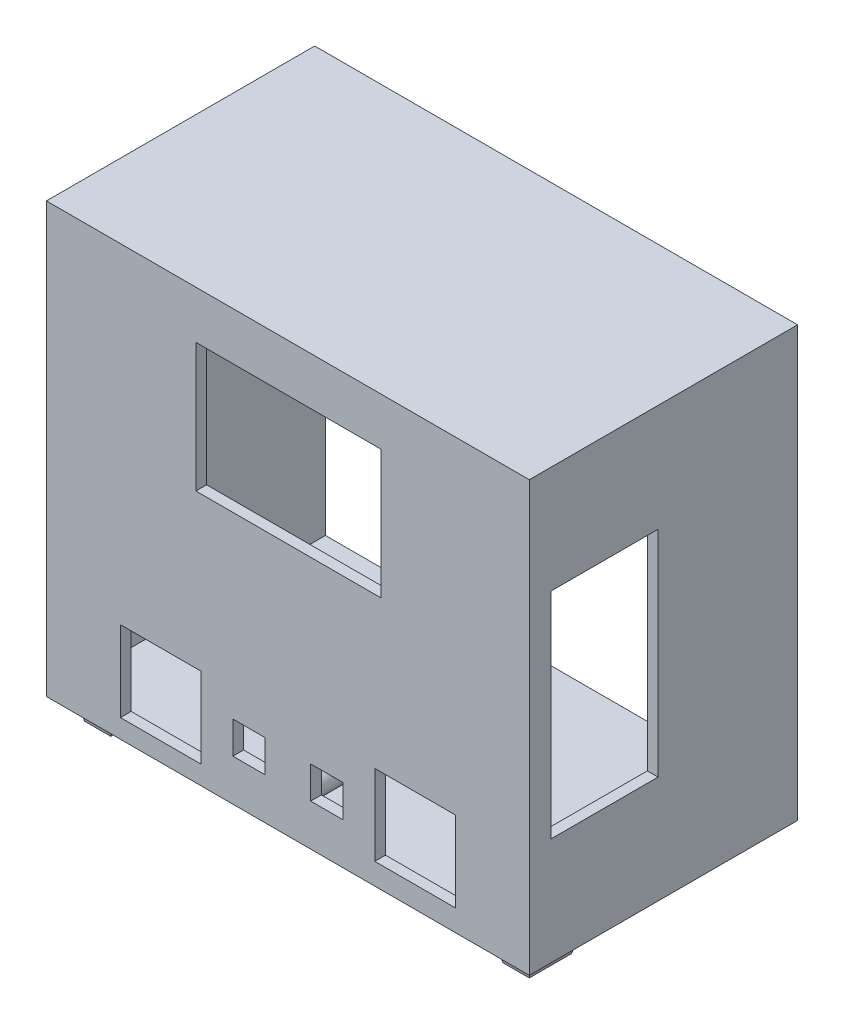
SolidWorks part; units mm, degrees
ref_plane "Front Plane" through (0, 0, 0) normal (0, 0, 1) x (1, 0, 0)
ref_plane "Top Plane" through (0, 0, 0) normal (0, 1, 0) x (1, 0, 0)
ref_plane "Right Plane" through (0, 0, 0) normal (1, 0, 0) x (0, 0, -1)
sketch "Sketch1" plane through (0, 0, 0) normal (0, 0, 1) x (1, 0, 0)
  line L1 (-45, -40) -> (45, -40)
  line L2 (-45, -40) -> (-45, 40)
  line L3 (-45, 40) -> (45, 40)
  line L4 (45, -40) -> (45, 40)
  line L5 (-45, -40) -> (45, 40) construction
  line L6 (-45, 40) -> (45, -40) construction
  point P0 (0, 0)
  dimension "D1" = 90
  dimension "D2" = 80
extrude "Boss-Extrude1" add sketch "Sketch1" along normal blind 50
shell "Shell1" thickness 2
sketch "Sketch2" plane through (0, 0, 50) normal (0, 0, 1) x (1, 0, 0)
  line L1 (-17.14, 31.1) -> (17.36, 31.1)
  line L2 (-17.14, 31.1) -> (-17.14, 7.1)
  line L3 (-17.14, 7.1) -> (17.36, 7.1)
  line L4 (17.36, 31.1) -> (17.36, 7.1)
  line L5 (-17.14, 31.1) -> (17.36, 7.1) construction
  line L6 (-17.14, 7.1) -> (17.36, 31.1) construction
  point P0 (0.11, 19.1)
extrude "Cut-Extrude" cut sketch "Sketch2" against normal blind 2
sketch "Sketch3" plane through (0, 0, 50) normal (0, 0, 1) x (1, 0, 0)
  line L0 (16.2, -21) -> (31.2, -21)
  line L1 (-31.2, -21.5) -> (-16.2, -21.5)
  line L2 (-31.2, -21.5) -> (-31.2, -36.5)
  line L3 (-31.2, -36.5) -> (-16.2, -36.5)
  line L4 (-16.2, -21.5) -> (-16.2, -36.5)
  line L5 (16.2, -21) -> (16.2, -36)
  line L6 (16.2, -36) -> (31.2, -36)
  line L7 (31.2, -21) -> (31.2, -36)
  line L16 (-10.25, -26.25) -> (-4.25, -26.25)
  line L17 (-10.25, -26.25) -> (-10.25, -32.25)
  line L18 (-10.25, -32.25) -> (-4.25, -32.25)
  line L19 (-4.25, -26.25) -> (-4.25, -32.25)
  line L20 (4.25, -26.25) -> (10.25, -26.25)
  line L21 (4.25, -26.25) -> (4.25, -32.25)
  line L22 (4.25, -32.25) -> (10.25, -32.25)
  line L23 (10.25, -26.25) -> (10.25, -32.25)
extrude "Cut-Extrude2" cut sketch "Sketch3" against normal blind 2
sketch "Sketch4" plane through (0, 0, 48) normal (0, 0, -1) x (-1, 0, 0)
  line L5 (-43, -38) -> (-43, 38) construction
  line L14 (43, -38) -> (-43, -38) construction
  line L15 (-43, 38) -> (43, 38) construction
  circle A0 centre (-34.5, -35) radius 2
  circle A1 centre (0, -34) radius 2
  circle A2 centre (-32.5, 31) radius 2
  dimension "D1" = 43
  dimension "D4" = 8.5
  dimension "D2" = 4
  dimension "D3" = 3
  dimension "D5" = 10.5
  dimension "D6" = 7
extrude "Boss-Extrude3" add sketch "Sketch4" along normal blind 10
sketch "Sketch7" plane through (0, -40, 0) normal (0, -1, 0) x (1, 0, 0)
  line L0 (-45, 50) -> (45, 50) construction
  line L1 (-42.5, 47.5) -> (-35.5, 47.5)
  line L2 (-42.5, 47.5) -> (-42.5, 37.5)
  line L3 (-42.5, 37.5) -> (-35.5, 37.5)
  line L4 (-35.5, 47.5) -> (-35.5, 37.5)
  line L5 (-45, 50) -> (-45, 0) construction
  line L6 (35.5, 47.5) -> (42.5, 47.5)
  line L7 (35.5, 47.5) -> (35.5, 37.5)
  line L8 (35.5, 37.5) -> (42.5, 37.5)
  line L9 (42.5, 47.5) -> (42.5, 37.5)
  line L10 (45, 50) -> (45, 0) construction
  dimension "D1" = 7
  dimension "D2" = 10
  dimension "D3" = 2.5
  dimension "D4" = 2.5
  dimension "D5" = 2.5
  dimension "D6" = 2.5
  dimension "D7" = 7
  dimension "D8" = 10
extrude "Boss-Extrude4" add sketch "Sketch7" along normal blind 4 draft 15
sketch "Sketch11" plane through (-45, 0, 0) normal (-1, 0, 0) x (0, 0, 1)
  line L0 (50, -40) -> (0, -40) construction
  line L1 (37, -3) -> (45, -3)
  line L2 (37, -3) -> (37, -15)
  line L3 (37, -15) -> (45, -15)
  line L4 (45, -3) -> (45, -15)
  line L6 (50, 40) -> (50, -40) construction
  dimension "D1" = 25
  dimension "D2" = 5
  dimension "D3" = 12
  dimension "D4" = 8
extrude "Cut-Extrude3" cut sketch "Sketch11" against normal blind 10
sketch "Sketch12" plane through (45, 0, 0) normal (1, 0, 0) x (0, 0, -1)
  line L0 (-50, -40) -> (0, -40) construction
  line L1 (-46, 20) -> (-26, 20)
  line L2 (-46, 20) -> (-46, -20)
  line L3 (-46, -20) -> (-26, -20)
  line L4 (-26, 20) -> (-26, -20)
  line L5 (-50, -40) -> (-50, 40) construction
  dimension "D1" = 20
  dimension "D2" = 40
  dimension "D3" = 20
  dimension "D4" = 4
extrude "Cut-Extrude4" cut sketch "Sketch12" against normal blind 10
hole_wizard "CSK for M3 Oval Head Machine Screw1" positions "Sketch13" profile "Sketch14" countersink size "M3" standard "ANSI Metric"
sketch "Sketch13" plane through (0, 0, 38) normal (0, 0, -1) x (-1, 0, 0)
  point P0 (-32.5, 31)
  point P3 (-34.5, -35)
  point P6 (0, -34)
sketch "Sketch14" plane through (32.5, 31, 38) normal (1, 0, 0) x (0, 1, 0)
  line L0 (0, 0) -> (0, 11.0215)
  line L1 (0, 11.0215) -> (1.7, 10)
  line L2 (1.7, 10) -> (1.7, 1.45)
  line L3 (1.7, 1.45) -> (3.15, 0)
  line L5 (3.15, 0) -> (0, 0)
  line L6 (-1.7, 1.45) -> (-3.15, 0) construction
  line L10 (0, 11.0215) -> (-1.7, 10) construction
  line L11 (0, -6.35) -> (0, 107.95) construction
  dimension "Hole Dia." = 3.4
  dimension "Hole Depth" = 10
  dimension "Near C'Sink Dia." = 6.3
  dimension "Near C'Sink Angle" = 90
  dimension "Drill Angle" = 118
